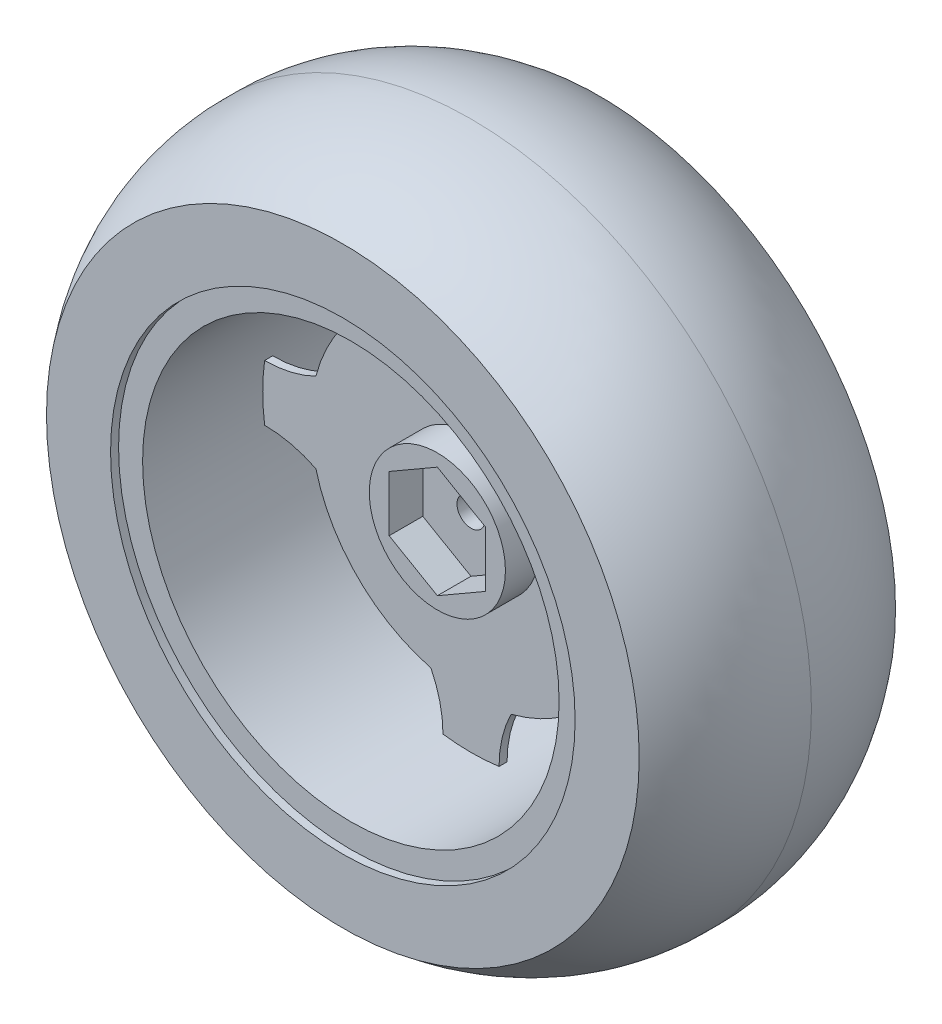
SolidWorks part; units mm, degrees
ref_plane "Front Plane" through (0, 0, 0) normal (0, 0, 1) x (1, 0, 0)
ref_plane "Top Plane" through (0, 0, 0) normal (0, 1, 0) x (1, 0, 0)
ref_plane "Right Plane" through (0, 0, 0) normal (1, 0, 0) x (0, 0, -1)
sketch "Sketch2" plane through (0, 0, 0) normal (0, 0, 1) x (1, 0, 0)
  circle A0 centre (0, 0) radius 20
extrude "Boss-Extrude1" add sketch "Sketch2" along normal blind 1
sketch "Sketch3" plane through (0, 0, 1) normal (0, 0, 1) x (1, 0, 0)
  line L2 (0, 6.95) -> (-6.0189, 3.475)
  line L3 (-6.0189, 3.475) -> (-6.0189, -3.475)
  line L4 (-6.0189, -3.475) -> (0, -6.95)
  line L5 (0, -6.95) -> (6.0189, -3.475)
  line L6 (6.0189, -3.475) -> (6.0189, 3.475)
  line L7 (6.0189, 3.475) -> (0, 6.95)
  circle A0 centre (0, 0) radius 8.5
  circle A1 centre (0, 0) radius 6.0189 construction
extrude "Boss-Extrude2" add sketch "Sketch3" along normal blind 4.2
sketch "Sketch7" plane through (0, 0, 0) normal (0, 0, -1) x (-1, 0, 0)
  line L0 (0, 0) -> (12.53, 0)
  line L1 (12.53, 0) -> (-12.53, 0)
  arc A1 (12.53, 0) -> (-12.53, 0) centre (0, 0) ccw
extrude "Boss-Extrude4" add sketch "Sketch7" along normal blind 2.5 contours L0 A1 L1
sketch "Sketch10" plane through (0, 0, 0) normal (0, -1, 0) x (1, 0, 0)
  line L0 (12.53, -2.5) -> (20, 0)
  line L1 (20, 0) -> (12.53, 0)
  line L3 (0, 0) -> (0, -2.5)
  line L4 (12.53, -2.5) -> (-12.53, -2.5) construction
  line L5 (12.53, -2.5) -> (0, -2.5)
  line L6 (12.53, 0) -> (0, 0)
revolve "Revolve1" add sketch "Sketch10" angle 360 about L3
sketch "Sketch11" plane through (0, 0, -2.5) normal (0, 0, -1) x (-1, 0, 0)
  line L5 (0, 0) -> (0, 9.6504)
  arc A1 (-25.7633, 3.5) -> (-25.7633, -3.5) centre (0, 0) ccw
  arc A2 (-19.3649, 5) -> (-19.3649, -5) centre (0, 0) ccw
  arc A3 (3.5, 25.7633) -> (5, 19.3649) centre (17.8966, 25.7633) ccw
  arc A4 (-3.5, 25.7633) -> (-5, 19.3649) centre (-17.8966, 25.7633) cw
  arc A5 (-3.5, -25.7633) -> (-5, -19.3649) centre (-17.8966, -25.7633) ccw
  arc A6 (3.5, -25.7633) -> (5, -19.3649) centre (17.8966, -25.7633) cw
  arc A7 (25.7633, -3.5) -> (19.3649, -5) centre (25.7633, -17.8966) ccw
  arc A8 (25.7633, 3.5) -> (19.3649, 5) centre (25.7633, 17.8966) cw
  arc A9 (-25.7633, -3.5) -> (-19.3649, -5) centre (-25.7633, -17.8966) cw
  arc A10 (-25.7633, 3.5) -> (-19.3649, 5) centre (-25.7633, 17.8966) ccw
  arc A11 (5, 19.3649) -> (-5, 19.3649) centre (0, 0) ccw
  arc A12 (3.5, 25.7633) -> (-3.5, 25.7633) centre (0, 0) ccw
  arc A13 (19.3649, -5) -> (19.3649, 5) centre (0, 0) ccw
  arc A14 (25.7633, -3.5) -> (25.7633, 3.5) centre (0, 0) ccw
  arc A15 (-5, -19.3649) -> (5, -19.3649) centre (0, 0) ccw
  arc A16 (-3.5, -25.7633) -> (3.5, -25.7633) centre (0, 0) ccw
extrude "Boss-Extrude5" add sketch "Sketch11" against normal blind 3.5 contours A7 A14 A8 A13 | A3 A12 A4 A11 | A5 A16 A6 A15 | A10 A1 A9 A2
sketch "Sketch13" plane through (0, 0, -2.5) normal (0, 0, -1) x (-1, 0, 0)
  arc A0 (-3.5, -25.7633) -> (3.5, -25.7633) centre (0, 0) ccw
  arc A1 (5, 19.3649) -> (-5, 19.3649) centre (0, 0) ccw
  arc A2 (25.7633, -3.5) -> (19.3649, -5) centre (25.7633, -17.8966) ccw
  arc A3 (25.7633, 3.5) -> (19.3649, 5) centre (25.7633, 17.8966) cw
  arc A4 (-25.7633, -3.5) -> (-19.3649, -5) centre (-25.7633, -17.8966) cw
  arc A5 (-25.7633, 3.5) -> (-19.3649, 5) centre (-25.7633, 17.8966) ccw
  arc A6 (3.5, -25.7633) -> (5, -19.3649) centre (17.8966, -25.7633) cw
  arc A7 (-3.5, -25.7633) -> (-5, -19.3649) centre (-17.8966, -25.7633) ccw
  arc A8 (3.5, 25.7633) -> (5, 19.3649) centre (17.8966, 25.7633) ccw
  arc A9 (-3.5, 25.7633) -> (-5, 19.3649) centre (-17.8966, 25.7633) cw
  arc A10 (-19.3649, 5) -> (-19.3649, -5) centre (0, 0) ccw
  arc A11 (-5, -19.3649) -> (5, -19.3649) centre (0, 0) ccw
  arc A12 (19.3649, -5) -> (19.3649, 5) centre (0, 0) ccw
  arc A13 (25.7633, -3.5) -> (25.7633, 3.5) centre (0, 0) ccw
  arc A14 (3.5, 25.7633) -> (-3.5, 25.7633) centre (0, 0) ccw
  arc A15 (-25.7633, 3.5) -> (-25.7633, -3.5) centre (0, 0) ccw
extrude "Cut-Extrude1" cut sketch "Sketch13" against normal blind 2.5 contours A0 A6 A11 A7 | A2 A12 A3 A13 | A4 A10 A5 A15 | A8 A1 A9 A14
sketch "Sketch14" plane through (0, 0, -2.5) normal (0, 0, -1) x (-1, 0, 0)
  circle A0 centre (0, 0) radius 1.75
extrude "Cut-Extrude2" cut sketch "Sketch14" against normal blind 20.5
sketch "Sketch15" plane through (0, 0, -2.5) normal (0, 0, -1) x (-1, 0, 0)
  line L0 (0, 0) -> (6, 0)
  line L1 (6, 0) -> (-6, 0)
  arc A0 (6, 0) -> (-6, 0) centre (0, 0) ccw
  arc A1 (5.5, 0) -> (-5.5, 0) centre (0, 0) ccw
extrude "Boss-Extrude7" add sketch "Sketch15" along normal blind 2.56 contours A1 L1 A0
sketch "Sketch18" plane through (0, 0, -2.5) normal (0, 0, -1) x (-1, 0, 0)
  line L4 (12.5284, 0.2) -> (5.9967, 0.2)
  line L5 (12.5284, -0.2) -> (5.9967, -0.2)
  circle A0 centre (0, 0) radius 12.53 construction
  arc A1 (12.5284, -0.2) -> (12.5284, 0.2) centre (0, 0) ccw
  arc A3 (5.9967, -0.2) -> (5.9967, 0.2) centre (0, 0) ccw
extrude "Boss-Extrude8" add sketch "Sketch18" along normal blind 2.56
sketch "Sketch19" plane through (0, -0.2, 0) normal (0, -1, 0) x (1, 0, 0)
  line L0 (-12.5284, -5.06) -> (-13.3868, -5.06)
  line L1 (-5.9967, -5.06) -> (-5.9967, -2.5) construction
  line L2 (-5.9967, -4.85) -> (-12.5284, -2.5)
  line L4 (-12.5284, -5.06) -> (-5.9967, -5.06)
  line L5 (-5.9967, -5.06) -> (-5.9967, -4.85)
  line L6 (-13.3868, -5.06) -> (-13.3868, -2.5)
  line L7 (-13.3868, -2.5) -> (-12.5284, -2.5)
extrude "Cut-Extrude4" cut sketch "Sketch19" against normal blind 1
pattern_circular "CirPattern3" count 4 over 360 about axis through (0, 0, 0) along (0, 0, 1) of "Boss-Extrude8", "Cut-Extrude4"
sketch "Sketch20" plane through (0, 0, -2.5) normal (0, 0, -1) x (-1, 0, 0)
  line L0 (-6, 0) -> (-5.5, 0)
  line L1 (5.5, 0) -> (6, 0)
  arc A0 (-5.5, 0) -> (5.5, 0) centre (0, 0) ccw
  arc A1 (-6, 0) -> (6, 0) centre (0, 0) ccw
extrude "Boss-Extrude10" add sketch "Sketch20" along normal blind 2.56
sketch "Sketch22" plane through (0, 0, 1) normal (0, 0, 1) x (1, 0, 0)
  circle A0 centre (0, 0) radius 26
  circle A1 centre (0, 0) radius 29
extrude "Boss-Extrude11" add sketch "Sketch22" along normal blind 15 separate body
sketch "Sketch23" plane through (0, 0, 1) normal (0, 0, -1) x (-1, 0, 0)
  circle A0 centre (0, 0) radius 29
  circle A1 centre (0, 0) radius 26
extrude "Boss-Extrude12" add sketch "Sketch23" along normal blind 15
sketch "Sketch25" plane through (0, 0, 1) normal (0, 0, 1) x (1, 0, 0)
  circle A0 centre (0, 0) radius 37
  circle A1 centre (0, 0) radius 42.5
  circle A2 centre (0, 0) radius 29
extrude "Boss-Extrude14" add sketch "Sketch25" along normal blind 16 contours A0 A2
sketch "Sketch26" plane through (0, 0, 1) normal (0, 0, -1) x (-1, 0, 0)
  circle A0 centre (0, 0) radius 37
  circle A1 centre (0, 0) radius 29
extrude "Boss-Extrude15" add sketch "Sketch26" along normal blind 16
sketch "Sketch27" plane through (0, 0, 17) normal (0, 0, 1) x (1, 0, 0)
  line L0 (0, 37) -> (0, 29)
  line L1 (0, 29) -> (4.9365, 29)
  line L2 (4.9365, 29) -> (4.9365, 37)
  line L3 (4.9365, 37) -> (0, 37)
  circle A0 centre (0, 0) radius 37 construction
  circle A1 centre (0, 0) radius 29 construction
extrude "Boss-Extrude16" add sketch "Sketch27" along normal blind 16
sketch "Sketch28" plane through (0, 0, 0) normal (-1, 0, 0) x (0, 0, 1)
  line L0 (-15, 37) -> (17, 37)
  line L2 (-15, 0) -> (17, 0)
  line L3 (-15, 37) -> (-15, -37) construction
  line L4 (17, -37) -> (17, 37) construction
  arc A1 (1, 42.5) -> (17, 37) centre (1.4483, 17.7813) cw
  arc A2 (1, 42.5) -> (-15, 37) centre (0.5517, 17.7813) ccw
revolve "Revolve2" add sketch "Sketch28" angle 360 mid plane about L2
sketch "Sketch29" plane through (4.9365, 0, 0) normal (1, 0, 0) x (0, 0, -1)
  line L1 (-33, 37) -> (-17, 37)
  line L2 (-33, 37) -> (-33, 29)
  line L3 (-33, 29) -> (-17, 29)
  line L4 (-17, 37) -> (-17, 29)
extrude "Cut-Extrude5" cut sketch "Sketch29" against normal blind 16
